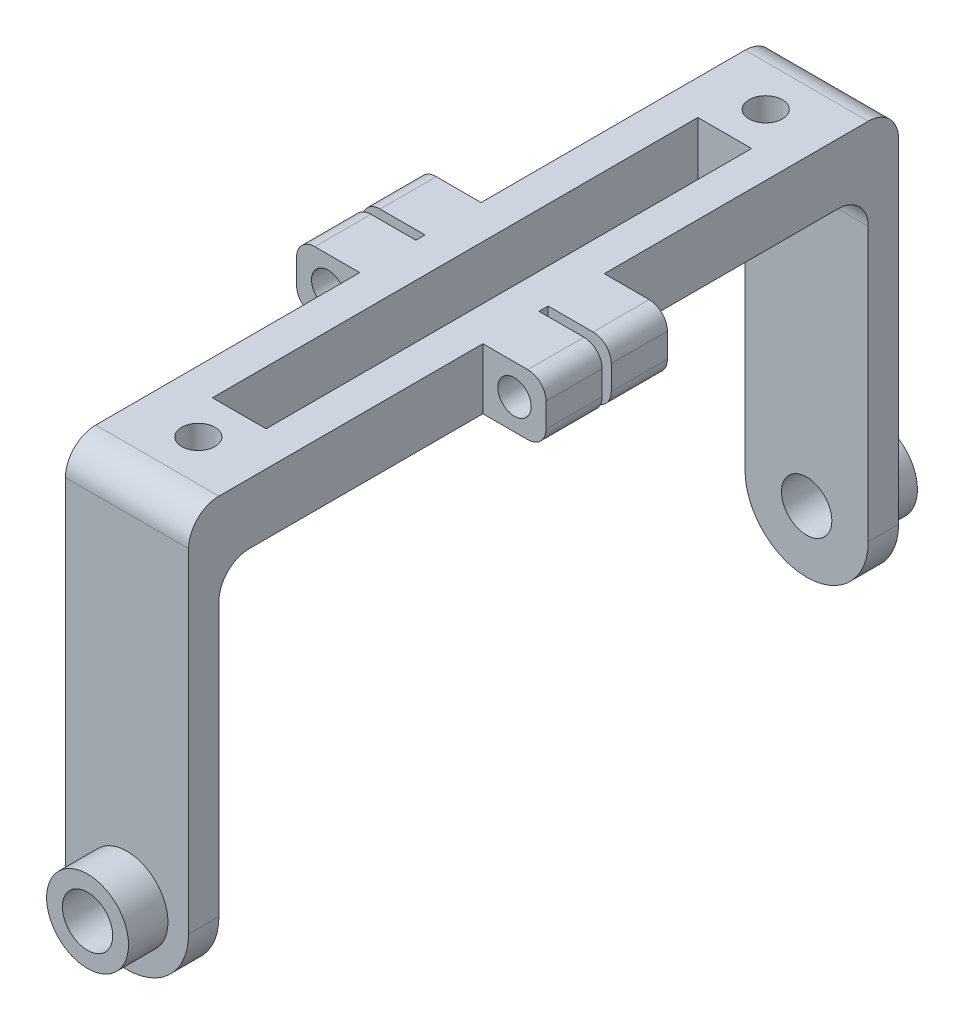
SolidWorks part; units mm, degrees
ref_plane "Front Plane" through (0, 0, 0) normal (0, 0, 1) x (1, 0, 0)
ref_plane "Top Plane" through (0, 0, 0) normal (0, 1, 0) x (1, 0, 0)
ref_plane "Right Plane" through (0, 0, 0) normal (1, 0, 0) x (0, 0, -1)
sketch "Sketch1" plane through (0, 0, 0) normal (0, 0, 1) x (1, 0, 0)
  circle A0 centre (-52, 0) radius 7.15
  circle A1 centre (-52, 0) radius 4.15
  dimension "D1" = 14.3
  dimension "D2" = 8.3
extrude "Boss-Extrude1" add sketch "Sketch1" against normal up to surface (5 mm away)
sketch "Sketch2" plane through (0, 0, -125) normal (0, 0, 1) x (1, 0, 0)
  circle A0 centre (-52, 0) radius 4.15 construction
  circle A1 centre (-52, 0) radius 7.15
  circle A2 centre (-52, 0) radius 7.15
  circle A3 centre (-52, 0) radius 4.15
  dimension "D1" = 0
extrude "Boss-Extrude2" add sketch "Sketch2" against normal up to surface (5 mm away) separate body
sketch "Sketch3" plane through (0, 0, -125) normal (0, 0, 1) x (1, 0, 0)
  circle A0 centre (-52, 0) radius 7.15 construction
  circle A1 centre (-52, 0) radius 4.15 construction
  circle A2 centre (-52, 0) radius 7.15
  circle A3 centre (-52, 0) radius 4.15
extrude "Boss-Extrude3" add sketch "Sketch3" along normal blind 1.5
sketch "Sketch4" plane through (0, 0, -5) normal (0, 0, -1) x (-1, 0, 0)
  circle A0 centre (52, 0) radius 4.15 construction
  circle A1 centre (52, 0) radius 7.15 construction
  circle A2 centre (52, 0) radius 4.15
  circle A3 centre (52, 0) radius 7.15
extrude "Boss-Extrude4" add sketch "Sketch4" along normal blind 1.5
sketch "Sketch5" plane through (0, 0, -6.5) normal (0, 0, -1) x (-1, 0, 0)
  line L0 (59.15, 0) -> (62.15, 0)
  line L1 (44.85, 0) -> (41.85, 0)
  line L2 (41.85, 0) -> (41.85, 40)
  line L3 (62.15, 0) -> (62.15, 40)
  line L4 (41.85, 40) -> (62.15, 40)
  circle A0 centre (52, 0) radius 7.15 construction
  circle A1 centre (52, 0) radius 10.15
  circle A2 centre (52, 0) radius 4.15
  circle M6 centre (52, 0) radius 7.15
  circle M7 centre (52, 0) radius 4.15
  dimension "D1" = 3
  dimension "D2" = 3
  dimension "D3" = 40
  dimension "D4" = 40
extrude "Boss-Extrude5" add sketch "Sketch5" along normal blind 5 contours M6 M7 | L1 A1 L0 M6 | L0 A1 L1 M6 | A1 L3 L4 L2
sketch "Sketch6" plane through (0, 0, -123.5) normal (0, 0, 1) x (1, 0, 0)
  line L3 (-62.15, 40) -> (-62.15, 0)
  line L4 (-41.85, 40) -> (-62.15, 40)
  line L5 (-41.85, 0) -> (-41.85, 40)
  line L6 (-62.15, 40) -> (-62.15, 0)
  line L7 (-41.85, 40) -> (-62.15, 40)
  line L8 (-41.85, 0) -> (-41.85, 40)
  circle A0 centre (-52, 0) radius 4.15 construction
  arc A1 (-62.15, 0) -> (-41.85, 0) centre (-52, 0) ccw
  arc A2 (-62.15, 0) -> (-41.85, 0) centre (-52, 0) ccw
  circle A3 centre (-52, 0) radius 4.15
  dimension "D1" = 0
extrude "Boss-Extrude6" add sketch "Sketch6" along normal blind 5
sketch "Sketch7" plane through (0, 0, -118.5) normal (0, 0, 1) x (1, 0, 0)
  line L0 (-41.85, 0) -> (-41.85, 40) construction
  line L1 (-62.15, 40) -> (-41.85, 40)
  line L2 (-62.15, 40) -> (-62.15, 30)
  line L3 (-62.15, 30) -> (-41.85, 30)
  line L4 (-41.85, 40) -> (-41.85, 30)
  dimension "D1" = 10
extrude "Boss-Extrude7" add sketch "Sketch7" along normal up to surface (107 mm away) up to face at (-52, 17.4625, -11.5)
sketch "Sketch8" plane through (0, 40, 0) normal (0, 1, 0) x (1, 0, 0)
  circle A1 centre (-52, 65) radius 4.15
  dimension "D1" = 8.3
extrude "Cut-Extrude1" cut sketch "Sketch8" against normal through all
fillet "Fillet1" radius 5 4 edges at (-52, 40, -6.5) (-52, 40, -123.5) (-52, 30, -118.5) (-52, 30, -11.5)
sketch "Sketch10" plane through (0, 40, 0) normal (0, 1, 0) x (1, 0, 0)
  line L0 (-56.225, 25) -> (-56.225, 105)
  line L1 (-56.225, 105) -> (-47.775, 105)
  line L2 (-47.775, 105) -> (-47.775, 25)
  line L3 (-52, 65) -> (-54.2764, 65)
  line L4 (-56.225, 25) -> (-47.775, 25)
  circle A0 centre (-52, 65) radius 4.225
  point P9 (-47.775, 65)
  point P10 (-56.225, 65)
  dimension "D1" = 8.45
  dimension "D2" = 40
extrude "Cut-Extrude3" cut sketch "Sketch10" against normal blind 18.9 contours A0 L0 L4 L2 | A0 L2 L1 L0
sketch "Sketch11" plane through (0, 0, 0) normal (0, 0, 1) x (1, 0, 0)
  circle A0 centre (-52, 0) radius 6.75
  circle A1 centre (-52, 0) radius 7.15
  dimension "D1" = 13.5
extrude "Cut-Extrude4" cut sketch "Sketch11" against normal up to surface (6.5 mm away) up to face at (-59.15, 0, -6.5)
sketch "Sketch12" plane through (0, 0, -130) normal (0, 0, -1) x (-1, 0, 0)
  circle A0 centre (52, 0) radius 7.15 construction
  circle A1 centre (52, 0) radius 7.15
  circle A2 centre (52, 0) radius 6.75 construction
  circle A3 centre (52, 0) radius 6.75
extrude "Cut-Extrude5" cut sketch "Sketch12" against normal up to surface (6.5 mm away) up to face at (-44.85, 0, -123.5)
sketch "Sketch13" plane through (0, 40, 0) normal (0, 1, 0) x (1, 0, 0)
  line L0 (-52, 11.5) -> (-52, 25)
  line L1 (-62.15, 11.5) -> (-41.85, 11.5) construction
  line L2 (-56.225, 25) -> (-47.775, 25) construction
  line L3 (-52, 105) -> (-52, 118.5)
  line L4 (-56.225, 105) -> (-47.775, 105) construction
  line L5 (-41.85, 118.5) -> (-62.15, 118.5) construction
  circle A0 centre (-52, 18.25) radius 2.75
  circle A1 centre (-52, 111.75) radius 2.75
  dimension "D1" = 5.5
  dimension "D2" = 5.5
extrude "Cut-Extrude6" cut sketch "Sketch13" against normal blind 18.9 contours L0 A0 | L3 A1 | L3 A1
sketch "Sketch14" plane through (-41.85, 0, 0) normal (1, 0, 0) x (0, 0, -1)
  line L0 (65, 30) -> (65, 40)
  line L2 (118.5, 40) -> (11.5, 40) construction
  line L3 (65.75, 30) -> (65.75, 40)
  line L4 (16.5, 30) -> (113.5, 30) construction
  line L5 (64.25, 30) -> (64.25, 40)
  line L6 (75, 30) -> (75, 40)
  line L7 (55, 30) -> (55, 40)
  line L8 (55, 40) -> (75, 40)
  line L9 (75, 30) -> (55, 30)
  line M2 (118.5, 40) -> (11.5, 40)
  line M8 (16.5, 30) -> (113.5, 30)
  dimension "D1" = 0.75
  dimension "D2" = 0.75
  dimension "D3" = 10
  dimension "D4" = 10
extrude "Boss-Extrude8" add sketch "Sketch14" along normal blind 0.4 contours L7 L5 M8 M2 | L6 L3 M8 M2
sketch "Sketch15" plane through (-62.15, 0, 0) normal (-1, 0, 0) x (0, 0, 1)
  line L0 (-55, 40) -> (-55, 30) construction
  line L1 (-55, 30) -> (-64.25, 30) construction
  line L2 (-64.25, 30) -> (-64.25, 40) construction
  line L3 (-64.25, 40) -> (-55, 40) construction
  line L4 (-65.75, 30) -> (-75, 30) construction
  line L5 (-75, 30) -> (-75, 40) construction
  line L6 (-75, 40) -> (-65.75, 40) construction
  line L7 (-65.75, 40) -> (-65.75, 30) construction
  line L8 (-55, 40) -> (-55, 30)
  line L9 (-55, 30) -> (-64.25, 30)
  line L10 (-64.25, 30) -> (-64.25, 40)
  line L11 (-64.25, 40) -> (-55, 40)
  line L12 (-65.75, 30) -> (-75, 30)
  line L13 (-75, 30) -> (-75, 40)
  line L14 (-75, 40) -> (-65.75, 40)
  line L15 (-65.75, 40) -> (-65.75, 30)
extrude "Boss-Extrude9" add sketch "Sketch15" along normal blind 0.4
sketch "Sketch17" plane through (-41.45, 0, 0) normal (1, 0, 0) x (0, 0, -1)
  line L4 (55, 40) -> (55, 30)
  line L5 (55, 30) -> (64.25, 30)
  line L6 (64.25, 30) -> (64.25, 40)
  line L7 (64.25, 40) -> (55, 40)
  line L8 (55, 40) -> (55, 30)
  line L9 (55, 30) -> (64.25, 30)
  line L10 (64.25, 30) -> (64.25, 40)
  line L11 (64.25, 40) -> (55, 40)
  line L12 (65.75, 30) -> (75, 30)
  line L13 (75, 30) -> (75, 40)
  line L14 (75, 40) -> (65.75, 40)
  line L15 (65.75, 40) -> (65.75, 30)
  line L16 (65.75, 30) -> (75, 30)
  line L17 (75, 30) -> (75, 40)
  line L18 (75, 40) -> (65.75, 40)
  line L19 (65.75, 40) -> (65.75, 30)
  dimension "D1" = 0
  dimension "D2" = 0
extrude "Boss-Extrude10" add sketch "Sketch17" along normal blind 10
sketch "Sketch18" plane through (0, 0, -75) normal (0, 0, -1) x (-1, 0, 0)
  line L0 (31.45, 35) -> (41.85, 35)
  line L1 (31.45, 30) -> (31.45, 40) construction
  circle A0 centre (36.65, 35) radius 2.75
  dimension "D1" = 5.5
extrude "Cut-Extrude7" cut sketch "Sketch18" against normal blind 26 contours L0 A0 | L0 A0
sketch "Sketch20" plane through (-62.55, 0, 0) normal (-1, 0, 0) x (0, 0, 1)
  line L4 (-65.75, 30) -> (-65.75, 40)
  line L5 (-65.75, 40) -> (-75, 40)
  line L6 (-75, 40) -> (-75, 30)
  line L7 (-75, 30) -> (-65.75, 30)
  line L8 (-65.75, 30) -> (-65.75, 40)
  line L9 (-65.75, 40) -> (-75, 40)
  line L10 (-75, 40) -> (-75, 30)
  line L11 (-75, 30) -> (-65.75, 30)
  line L12 (-55, 40) -> (-64.25, 40)
  line L13 (-64.25, 40) -> (-64.25, 30)
  line L14 (-64.25, 30) -> (-55, 30)
  line L15 (-55, 30) -> (-55, 40)
  line L16 (-55, 40) -> (-64.25, 40)
  line L17 (-64.25, 40) -> (-64.25, 30)
  line L18 (-64.25, 30) -> (-55, 30)
  line L19 (-55, 30) -> (-55, 40)
  dimension "D1" = 0
  dimension "D2" = 0
extrude "Boss-Extrude11" add sketch "Sketch20" along normal blind 10
sketch "Sketch21" plane through (0, 0, -75) normal (0, 0, -1) x (-1, 0, 0)
  line L0 (72.55, 35) -> (62.15, 35)
  line L1 (72.55, 40) -> (72.55, 30) construction
  circle A0 centre (67.35, 35) radius 2.75
  dimension "D1" = 5.5
extrude "Cut-Extrude8" cut sketch "Sketch21" against normal through all both and the other way through all contours L0 A0
fillet "Fillet2" radius 3 8 edges at (-72.55, 30, -70.375) (-72.55, 40, -70.375) (-72.55, 30, -59.625) (-72.55, 40, -59.625) (-31.45, 30, -70.375) (-31.45, 30, -59.625) (-31.45, 40, -59.625) (-31.45, 40, -70.375)
sketch "Sketch23" plane through (-41.85, 0, 0) normal (1, 0, 0) x (0, 0, -1)
  line L0 (6.5, 17.5) -> (123.5, 17.5)
  line L1 (6.5, 0) -> (6.5, 35) construction
  line L2 (123.5, 0) -> (123.5, 35) construction
  line L3 (123.5, 17.5) -> (123.5, 19.5)
  line L4 (123.5, 19.5) -> (6.5, 19.5)
  line L5 (6.5, 19.5) -> (6.5, 17.5)
  dimension "D1" = 2
extrude "Cut-Extrude9" cut sketch "Sketch23" against normal blind 37
move or copy body "Body-Move/Copy1" bodies to move or copy 119 copy no translate (0, 20, 0)
sketch "Sketch24" plane through (0, 17.5, 0) normal (0, 1, 0) x (1, 0, 0)
  line L0 (-62.15, 6.5) -> (-41.85, 6.5) construction
  line L1 (-41.85, 6.5) -> (-41.85, 11.5) construction
  line L2 (-41.85, 11.5) -> (-62.15, 11.5) construction
  line L3 (-62.15, 11.5) -> (-62.15, 6.5) construction
  line L4 (-62.15, 118.5) -> (-41.85, 118.5) construction
  line L5 (-41.85, 118.5) -> (-41.85, 123.5) construction
  line L6 (-41.85, 123.5) -> (-62.15, 123.5) construction
  line L7 (-62.15, 123.5) -> (-62.15, 118.5) construction
  line L8 (-62.15, 6.5) -> (-41.85, 6.5)
  line L9 (-41.85, 6.5) -> (-41.85, 11.5)
  line L10 (-41.85, 11.5) -> (-62.15, 11.5)
  line L11 (-62.15, 11.5) -> (-62.15, 6.5)
  line L12 (-62.15, 118.5) -> (-41.85, 118.5)
  line L13 (-41.85, 118.5) -> (-41.85, 123.5)
  line L14 (-41.85, 123.5) -> (-62.15, 123.5)
  line L15 (-62.15, 123.5) -> (-62.15, 118.5)
extrude "Boss-Extrude12" add sketch "Sketch24" along normal up to surface (22 mm away) up to face at (-52, 39.5, -9)
sketch "Sketch25" plane through (-56.225, 0, 0) normal (1, 0, 0) x (0, 0, -1)
  line L4 (25, 50) -> (105, 50)
  line L5 (105, 50) -> (105, 60)
  line L6 (105, 60) -> (25, 60)
  line L7 (25, 60) -> (25, 50)
  line L8 (25, 50) -> (105, 50)
  line L9 (105, 50) -> (105, 60)
  line L10 (105, 60) -> (25, 60)
  line L11 (25, 60) -> (25, 50)
  dimension "D1" = 0
extrude "Cut-Extrude10" cut sketch "Sketch25" against normal blind 0.2
sketch "Sketch26" plane through (-47.775, 0, 0) normal (-1, 0, 0) x (0, 0, 1)
  line L4 (-105, 50) -> (-25, 50)
  line L5 (-25, 50) -> (-25, 60)
  line L6 (-25, 60) -> (-105, 60)
  line L7 (-105, 60) -> (-105, 50)
  line L8 (-105, 50) -> (-25, 50)
  line L9 (-25, 50) -> (-25, 60)
  line L10 (-25, 60) -> (-105, 60)
  line L11 (-105, 60) -> (-105, 50)
  dimension "D1" = 0
extrude "Cut-Extrude11" cut sketch "Sketch26" against normal blind 0.2
